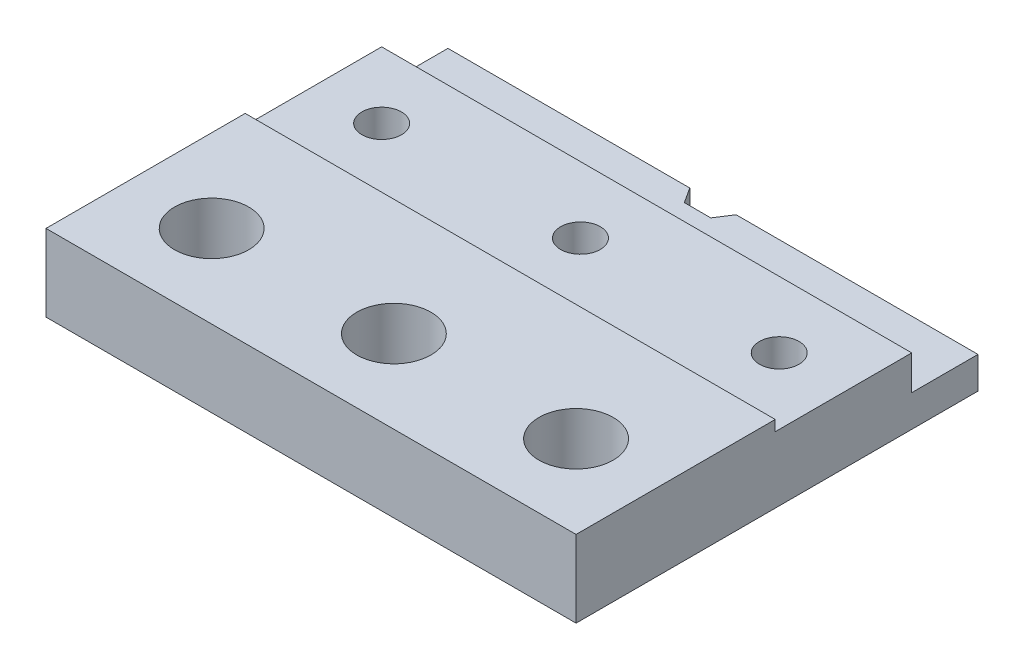
SolidWorks part; units mm, degrees
material "D2"
ref_plane "Alzado" through (0, 0, 0) normal (0, 0, 1) x (1, 0, 0)
ref_plane "Planta" through (0, 0, 0) normal (0, 1, 0) x (1, 0, 0)
ref_plane "Vista lateral" through (0, 0, 0) normal (1, 0, 0) x (0, 0, -1)
sketch "Croquis1" plane through (0, 0, 0) normal (0, 1, 0) x (1, 0, 0)
  line L1 (25.4, 19.2596) -> (-25.4, 19.2596)
  line L2 (25.4, 19.2596) -> (25.4, -19.2596)
  line L3 (25.4, -19.2596) -> (-25.4, -19.2596)
  line L4 (-25.4, 19.2596) -> (-25.4, -19.2596)
  line L5 (0, -19.2596) -> (0, 19.2595) construction
  line L6 (25.4, 0) -> (-25.4, 0) construction
  point P80 (0, 0)
  dimension "D1" = 50.8
  dimension "D2" = 38.5191
extrude "Saliente-Extruir1" add sketch "Croquis1" along normal blind 7.366
sketch "Croquis2" plane through (25.4, 0, 0) normal (1, 0, 0) x (0, 0, -1)
  line L0 (19.2596, 3.048) -> (12.9095, 3.048)
  line L1 (19.2596, 7.366) -> (19.2596, 0) construction
  line L2 (12.9095, 3.048) -> (12.9095, 6.35)
  line L3 (12.9095, 6.35) -> (-0.1715, 6.35)
  line L4 (-0.1715, 6.35) -> (-0.1715, 7.366)
  line L5 (-19.2596, 7.366) -> (19.2596, 7.366) construction
  line L6 (-0.1715, 7.366) -> (19.2596, 7.366)
  line L7 (19.2596, 7.366) -> (19.2596, 3.048)
  line L8 (-19.2596, 0) -> (19.2596, 0) construction
  line L9 (-19.2596, 7.366) -> (-19.2596, 0) construction
  dimension "D1" = 3.048
  dimension "D2" = 1.016
  dimension "D3" = 19.0881
  dimension "D4" = 32.1691
extrude "Cortar-Extruir1" cut sketch "Croquis2" against normal through all
sketch "Croquis3" plane through (0, 7.366, 0) normal (0, 1, 0) x (1, 0, 0)
  line L0 (-17.4625, -11.3221) -> (17.4625, -11.322) construction
  line L2 (0, -11.322) -> (0, -19.2596) construction
  line L3 (-25.4, -19.2596) -> (25.4, -19.2596) construction
  point P0 (17.4625, -11.322)
  point P2 (0, -11.322)
  point P4 (-17.4625, -11.3221)
  dimension "D1" = 7.9375
  dimension "D2" = 34.925
hole_wizard "Taladros de espiga de 5/16 (0.28)1" positions "Croquis3" profile "Croquis4" hole size "5/16" standard "Ansi Inch" end condition through all
sketch "Croquis4" plane through (17.4625, 7.366, 11.322) normal (1, 0, 0) x (0, 0, 1)
  line L0 (0, 0) -> (0, 7.366)
  line L1 (0, 7.366) -> (3.556, 7.366)
  line L2 (3.556, 7.366) -> (3.556, 0)
  line L5 (3.556, 0) -> (0, 0)
  line L11 (0, -6.35) -> (0, 107.95) construction
  dimension "Diámetro de taladro hasta el siguiente" = 7.112
  dimension "Profundidad de taladro hasta el siguiente" = 7.366
sketch "Croquis5" plane through (0, 3.048, 0) normal (0, 1, 0) x (1, 0, 0)
  line L0 (-2.2225, 19.2596) -> (-1.27, 17.7864)
  line L1 (-25.4, 19.2596) -> (25.4, 19.2596) construction
  line L2 (-1.27, 17.7864) -> (1.27, 17.7864)
  line L3 (1.27, 17.7864) -> (2.2225, 19.2596)
  line L4 (2.2225, 19.2596) -> (-2.2225, 19.2596)
  line L5 (0, 19.2596) -> (0, 17.7864) construction
  dimension "D1" = 4.445
  dimension "D2" = 2.54
  dimension "D3" = 1.4732
extrude "Cortar-Extruir2" cut sketch "Croquis5" against normal through all
sketch "Croquis6" plane through (0, 6.35, 0) normal (0, 1, 0) x (1, 0, 0)
  line L0 (-19.05, 6.5595) -> (19.05, 6.5596) construction
  line L2 (0, 6.5595) -> (0, 0) construction
  line L4 (-25.4, -19.2596) -> (25.4, -19.2596) construction
  point P0 (19.05, 6.5596)
  point P2 (0, 6.5595)
  point P4 (-19.05, 6.5595)
  dimension "D1" = 38.1
  dimension "D2" = 25.8191
hole_wizard "Taladro roscado #10-241" positions "Croquis6" profile "Croquis7" tap size "#10-24" standard "Ansi Inch" end condition through all
sketch "Croquis7" plane through (19.05, 6.35, -6.5596) normal (1, 0, 0) x (0, 0, 1)
  line L0 (0, 0) -> (0, 6.35)
  line L1 (0, 6.35) -> (1.8986, 6.35)
  line L2 (1.8986, 6.35) -> (1.8986, 0)
  line L5 (1.8986, 0) -> (0, 0)
  line L11 (0, -6.35) -> (0, 107.95) construction
  dimension "Diámetro de perforador para roscar hasta el siguiente" = 3.7973
  dimension "Profundidad de perforador para roscar hasta el siguiente" = 6.35
cosmetic thread "Rosca de taladro1" parameters "D2"=4.826
cosmetic thread "Rosca de taladro2" parameters "D2"=4.826
cosmetic thread "Rosca de taladro3" parameters "D2"=4.826
